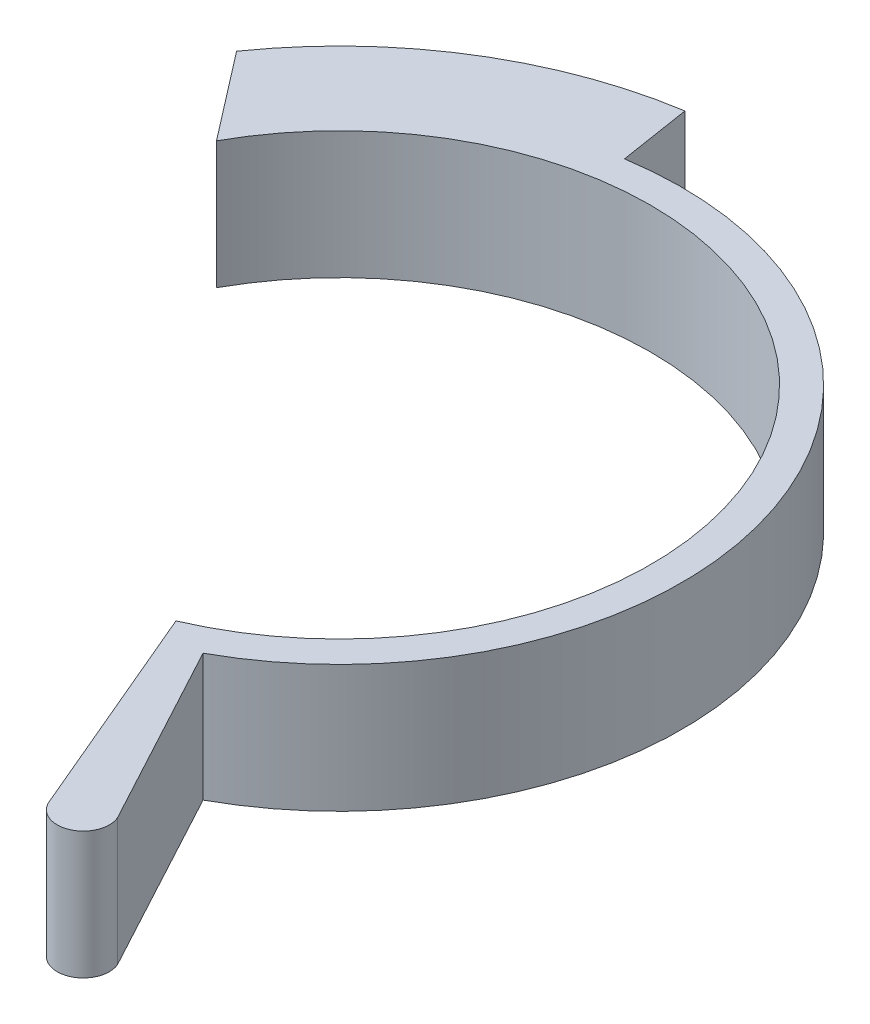
SolidWorks part; units mm, degrees
ref_plane "Plano frontal" through (0, 0, 0) normal (0, 0, 1) x (1, 0, 0)
ref_plane "Plano superior" through (0, 0, 0) normal (0, 1, 0) x (1, 0, 0)
ref_plane "Plano direito" through (0, 0, 0) normal (1, 0, 0) x (0, 0, -1)
sketch "Esboço1" plane through (0, 0, 0) normal (0, 1, 0) x (1, 0, 0)
  line L2 (12.9939, -30.3341) -> (11.8236, -27.5718)
  line L4 (0, 0) -> (0, -30) construction
  line L5 (0, 0) -> (5.8657, 32.4745) construction
  line L6 (3, -40) -> (2.9916, -39.888)
  line L10 (-6.2116, 39.5148) -> (-5.1245, 32.5997)
  line L12 (-28.2685, 17.0158) -> (-32.8001, 22.8944)
  line L13 (12.9939, -30.3341) -> (20.7957, -48.7497)
  line L14 (-27.9737, 16.6334) -> (-20.8945, 7.45) construction
  line L16 (-28.2685, 17.0158) -> (-26.2906, 14.4501)
  line L17 (15.7246, -36.7796) -> (14.5543, -34.0173) construction
  line L19 (25.4536, -46.854) -> (15.8233, -28.959)
  arc A2 (11.8236, -27.5718) -> (-26.2906, 14.4501) centre (0, 0) ccw
  arc A11 (-6.2116, 39.5148) -> (-32.8001, 22.8944) centre (0, 0) ccw
  arc A15 (-6.2116, 39.5148) -> (-32.8001, 22.8944) centre (0, 0) ccw
  arc A18 (15.8233, -28.959) -> (-5.1245, 32.5997) centre (0, 0) ccw
  arc A20 (20.7957, -48.7497) -> (25.1986, -46.3802) centre (23.1246, -47.8018) ccw
  arc A21 (27.8629, -17.6821) -> (-5.1245, 32.5997) centre (0, 0) ccw
  arc A22 (27.8629, -17.6821) -> (12.6543, 30.4774) centre (0, 0) ccw
  arc A25 (15.8233, -28.959) -> (26.071, -20.2312) centre (0, 0) ccw
  arc A26 (15.8233, -28.959) -> (26.071, -20.2312) centre (0, 0) ccw
  dimension "D1" = 5
  dimension "D2" = 20
  dimension "D3" = 30
extrude "Ressalto-extrusão1" add sketch "Esboço1" along normal blind 12.26
